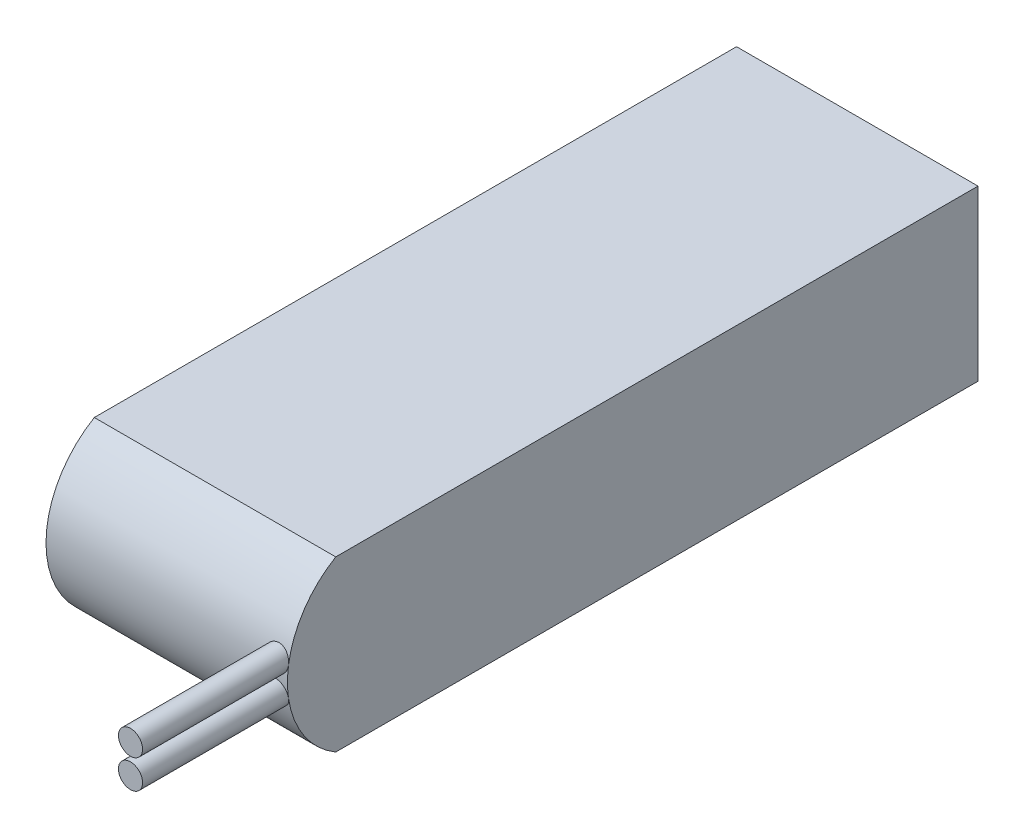
SolidWorks part; units mm, degrees
ref_plane "Plan de face" through (0, 0, 0) normal (0, 0, 1) x (1, 0, 0)
ref_plane "Plan de dessus" through (0, 0, 0) normal (0, 1, 0) x (1, 0, 0)
ref_plane "Plan de droite" through (0, 0, 0) normal (1, 0, 0) x (0, 0, -1)
sketch "Esquisse1" plane through (0, 0, 0) normal (0, 0, 1) x (1, 0, 0)
  line L1 (0, 0) -> (50, 0)
  line L2 (0, 0) -> (0, 35)
  line L3 (0, 35) -> (50, 35)
  line L4 (50, 0) -> (50, 35)
  dimension "D1" = 35
  dimension "D2" = 50
extrude "Boss.-Extru.1" add sketch "Esquisse1" along normal blind 133
sketch "Esquisse2" plane through (50, 0, 0) normal (1, 0, 0) x (0, 0, -1)
  line L0 (-133, 0) -> (-133, 35) construction
  line L1 (-133, 35) -> (-133, 0)
  arc A0 (-133, 35) -> (-133, 0) centre (-122.6875, 17.5) ccw
  point P7 (-143, 17.5)
  dimension "D1" = 10
extrude "Boss.-Extru.2" add sketch "Esquisse2" against normal up to vertex (50 mm away) up to point (0, 35, 133)
sketch "Esquisse3" plane through (0, 0, 0) normal (0, 0, -1) x (-1, 0, 0)
  line L0 (-50, 0) -> (-50, 35) construction
  line L1 (-47.5, 20.5) -> (-47.5, 14.5) construction
  line L2 (-50, 17.5) -> (0, 17.5) construction
  line L3 (0, 35) -> (0, 0) construction
  circle A0 centre (-47.5, 20.5) radius 2.5
  circle A1 centre (-47.5, 14.5) radius 2.5
  point P9 (-47.5, 14.5)
  dimension "D1" = 5
  dimension "D2" = 3
  dimension "D3" = 3
extrude "Boss.-Extru.3" add sketch "Esquisse3" against normal blind 173
